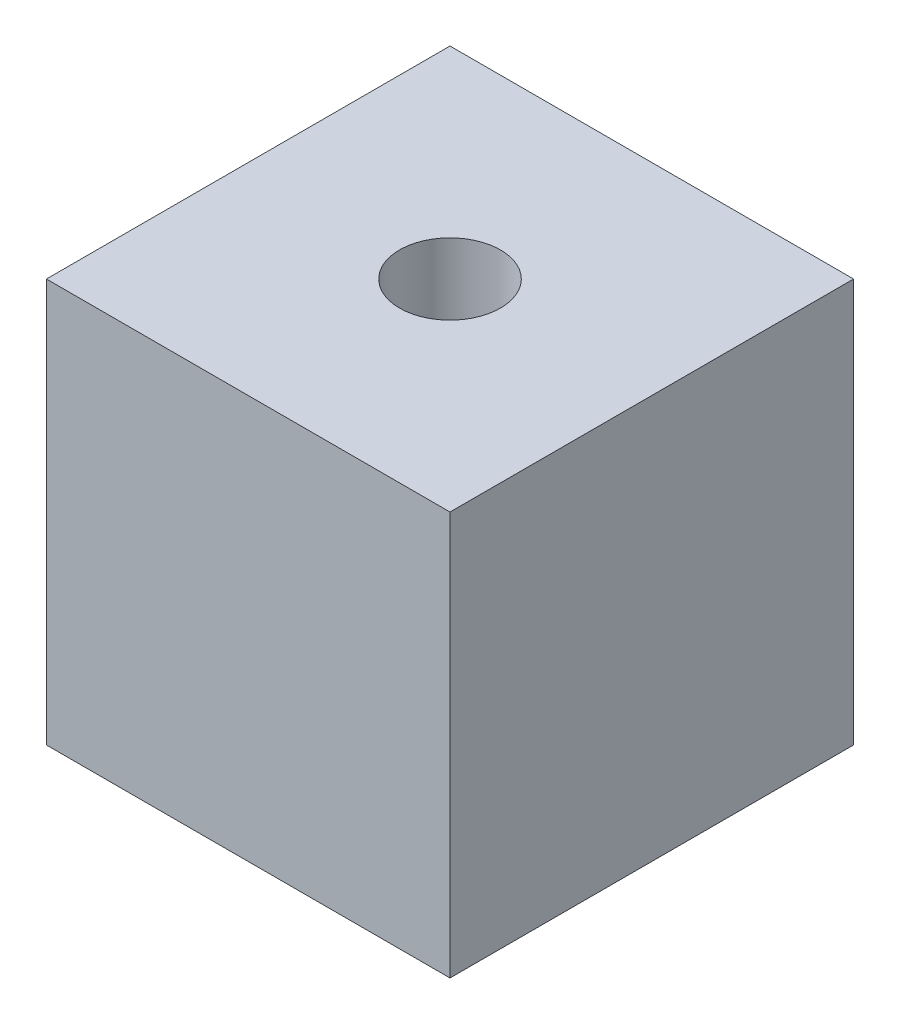
SolidWorks part; units mm, degrees
ref_plane "Front Plane" through (0, 0, 0) normal (0, 0, 1) x (1, 0, 0)
ref_plane "Top Plane" through (0, 0, 0) normal (0, 1, 0) x (1, 0, 0)
ref_plane "Right Plane" through (0, 0, 0) normal (1, 0, 0) x (0, 0, -1)
sketch "Sketch1" plane through (0, 0, 0) normal (0, 1, 0) x (1, 0, 0)
  line L0 (0, 25.4) -> (25.4, 0) construction
  line L1 (0, 0) -> (25.4, 0)
  line L2 (0, 0) -> (0, 25.4)
  line L3 (0, 25.4) -> (25.4, 25.4)
  line L4 (25.4, 0) -> (25.4, 25.4)
  line L5 (0, 0) -> (25.4, 25.4) construction
  circle A0 centre (12.7, 12.7) radius 3.175
  dimension "D3" = 6.35
  dimension "D1" = 25.4
  dimension "D2" = 25.4
extrude "Boss-Extrude1" add sketch "Sketch1" along normal blind 25.4
